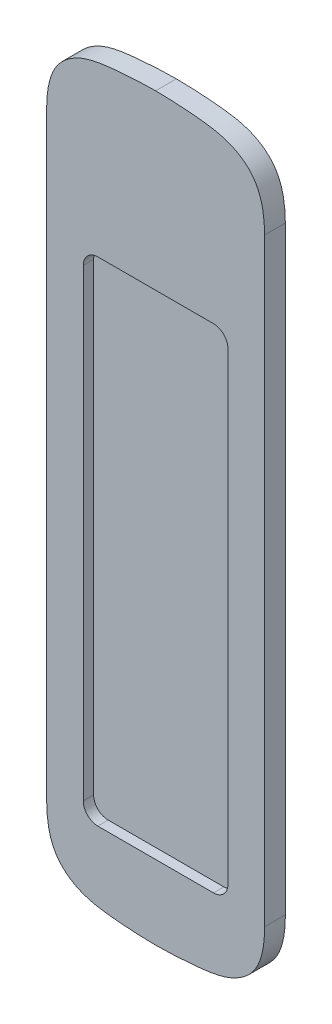
SolidWorks part; units mm, degrees
ref_plane "Front" through (0, 0, 0) normal (0, 0, 1) x (1, 0, 0)
ref_plane "Top" through (0, 0, 0) normal (0, 1, 0) x (1, 0, 0)
ref_plane "Right" through (0, 0, 0) normal (1, 0, 0) x (0, 0, -1)
sketch "草图1" plane through (0, 0, 0) normal (0, 0, 1) x (1, 0, 0)
  line L2 (-5.2688, -23.3957) -> (-5.2688, -52.2963)
  line L3 (5.2442, -52.2963) -> (5.2442, -23.3957)
  line L8 (-5.2688, -23.3957) -> (-5.2688, -52.2963)
  line L9 (5.2442, -52.2963) -> (5.2442, -23.3957)
  spline S4 degree 3 poles (-5877.6183, 1147.858) (-3.1215, -49.6442) (-15.7593, -56.8862) (2.3591, -55.5673) (3.3747, -55.3732) (4.1578, -55.0037) (18.2188, -41.401) (-185.1176, 117.9199) (3167.0105, -5150.7551) knots -6.893951 -6.893951 -6.893951 -6.893951 0.168659 0.347793 0.462796 0.595546 0.69884 8.374974 8.374974 8.374974 8.374974 only from (-0.0123, -55.6929) to (5.2442, -52.2963)
  spline S5 degree 3 poles (-3166.9758, -5150.662) (185.0907, 117.9181) (-18.2432, -41.4011) (-4.1823, -55.0037) (-3.3993, -55.3732) (-2.3837, -55.5673) (15.7347, -56.8862) (3.097, -49.6442) (5877.5941, 1147.8581) knots -7.374929 -7.374929 -7.374929 -7.374929 0.30116 0.404454 0.537204 0.652207 0.831341 7.893951 7.893951 7.893951 7.893951 only from (-5.2688, -52.2963) to (-0.0123, -55.6929)
  spline S6 degree 3 poles (5877.5937, -1223.55) (3.097, -26.0478) (15.7347, -18.8058) (-2.3837, -20.1247) (-3.3993, -20.3188) (-4.1823, -20.6883) (-18.2433, -34.291) (185.093, -193.6119) (-3167.035, 5075.0631) knots -6.893951 -6.893951 -6.893951 -6.893951 0.168659 0.347793 0.462796 0.595546 0.69884 8.374974 8.374974 8.374974 8.374974 only from (-0.0123, -19.9991) to (-5.2688, -23.3957)
  spline S7 degree 3 poles (3166.9512, 5074.97) (-185.1152, -193.6101) (18.2187, -34.2909) (4.1578, -20.6883) (3.3747, -20.3188) (2.3591, -20.1247) (-15.7593, -18.8058) (-3.1215, -26.0478) (-5877.6186, -1223.5501) knots -7.374929 -7.374929 -7.374929 -7.374929 0.30116 0.404454 0.537204 0.652207 0.831341 7.893951 7.893951 7.893951 7.893951 only from (5.2442, -23.3957) to (-0.0123, -19.9991)
  spline S8 degree 3 poles (-0.0123, -55.6929) (0.4331, -55.6929) (1.2193, -55.6503) (2.3591, -55.5673) (3.3747, -55.3732) (4.1578, -55.0037) (5.1125, -54.0801) (5.2442, -52.9903) (5.2442, -52.2963) knots 0 0 0 0 0.168659 0.347793 0.462796 0.595546 0.69884 1 1 1 1
  spline S9 degree 3 poles (-5.2688, -52.2963) (-5.2688, -52.9903) (-5.137, -54.0801) (-4.1823, -55.0037) (-3.3993, -55.3732) (-2.3837, -55.5673) (-1.2439, -55.6503) (-0.4576, -55.6929) (-0.0123, -55.6929) knots 0 0 0 0 0.30116 0.404454 0.537204 0.652207 0.831341 1 1 1 1
  spline S10 degree 3 poles (-0.0123, -19.9991) (-0.4576, -19.9991) (-1.2439, -20.0417) (-2.3837, -20.1247) (-3.3993, -20.3188) (-4.1823, -20.6883) (-5.137, -21.6119) (-5.2688, -22.7017) (-5.2688, -23.3957) knots 0 0 0 0 0.168659 0.347793 0.462796 0.595546 0.69884 1 1 1 1
  spline S11 degree 3 poles (5.2442, -23.3957) (5.2442, -22.7017) (5.1125, -21.6119) (4.1578, -20.6883) (3.3747, -20.3188) (2.3591, -20.1247) (1.2193, -20.0417) (0.4331, -19.9991) (-0.0123, -19.9991) knots 0 0 0 0 0.30116 0.404454 0.537204 0.652207 0.831341 1 1 1 1
  dimension "D1" = 0
extrude "凸台-拉伸1" add sketch "草图1" along normal blind 1
sketch "草图5"
sketch "草图3" [suppressed] plane through (0, 0, 1) normal (0, 0, 1) x (1, 0, 0)
  line L1 (-2.2247, -52.5921) -> (0.7217, -52.5921)
  line L2 (-2.2247, -52.5921) -> (-2.2247, -51.126)
  line L3 (-2.2247, -51.126) -> (0.7217, -51.126)
  line L4 (0.7217, -52.5921) -> (0.7217, -51.126)
  line L5 (-2.2247, -52.5921) -> (0.7217, -51.126) construction
  line L6 (-2.2247, -51.126) -> (0.7217, -52.5921) construction
  point P0 (-0.7515, -51.859)
ref_plane "基准面1" through (0, 0, 1.01) normal (0, 0, 1) x (1, 0, 0)
sketch "草图4" plane through (0, 0, 0.51) normal (0, 0, 1) x (1, 0, 0)
  line L0 (-37.9719, -42.3448) -> (303.3614, -42.3448) construction
  line L1 (0, -24.0288) -> (0, -24.0288) construction
sketch "草图6" plane through (0, 0, 1) normal (0, 0, 1) x (1, 0, 0)
  line L0 (-0.0123, -55.6929) -> (-0.0123, -19.9991) construction
  line L1 (-0.0123, -19.6991) -> (-0.0123, -16.2142) construction
  line L2 (-3.5023, -28.332) -> (3.4777, -28.332)
  line L3 (-3.5023, -28.332) -> (-3.5023, -52.112)
  line L4 (-3.5023, -52.112) -> (3.4777, -52.112)
  line L5 (3.4777, -28.332) -> (3.4777, -52.112)
  line L6 (-3.5023, -28.332) -> (3.4777, -52.112) construction
  line L7 (-3.5023, -52.112) -> (3.4777, -28.332) construction
  line L9 (4.3377, -52.912) -> (-4.3623, -52.912) construction
  line L10 (4.3377, -52.912) -> (4.3377, -23.912) construction
  line L12 (2.6497, -51.082) -> (-2.6743, -51.082) construction
  line L16 (2.7777, -29.032) -> (-2.8023, -29.032)
  line L17 (2.7777, -29.032) -> (2.7777, -51.412)
  line L18 (2.7777, -51.412) -> (-2.8023, -51.412)
  line L19 (-2.8023, -29.032) -> (-2.8023, -51.412)
  line L20 (2.7777, -29.032) -> (-2.8023, -51.412) construction
  line L21 (2.7777, -51.412) -> (-2.8023, -29.032) construction
  point P1 (-0.0123, -38.4775)
  point P14 (-0.0123, -28.332)
  point P25 (-0.0123, -40.222)
  dimension "D1" = 1.03
  dimension "D2" = 23.78
  dimension "D3" = 0.8
  dimension "D4" = 5.58
  dimension "D5" = 0.86
  dimension "D6" = 1.5
  dimension "D7" = 22.38
extrude "切除-拉伸1" cut sketch "草图6" against normal blind 0.5 contours L3 L2 L5 L4
fillet "圆角1" radius 0.7 4 edges at (-3.5023, -28.332, 0.75) (-3.5023, -52.112, 0.75) (3.4777, -52.112, 0.75) (3.4777, -28.332, 0.75)
